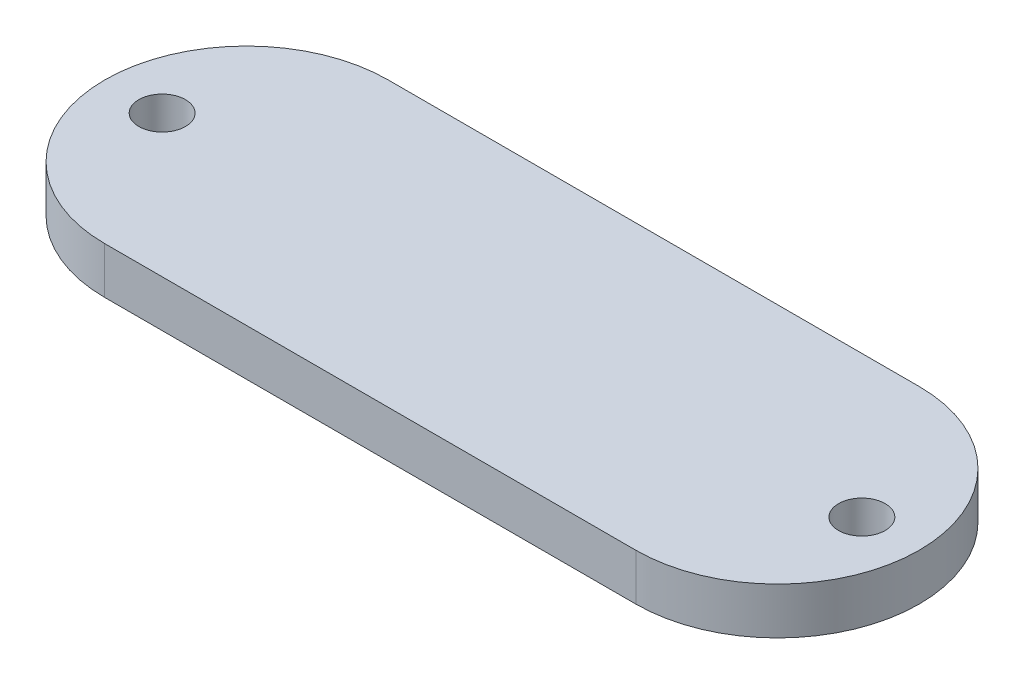
SolidWorks part; units mm, degrees
ref_plane "Front Plane" through (0, 0, 0) normal (0, 0, 1) x (1, 0, 0)
ref_plane "Top Plane" through (0, 0, 0) normal (0, 1, 0) x (1, 0, 0)
ref_plane "Right Plane" through (0, 0, 0) normal (1, 0, 0) x (0, 0, -1)
sketch "Sketch1" plane through (0, 0, 0) normal (0, 1, 0) x (1, 0, 0)
  line L1 (0, 19.75) -> (37, 19.75)
  line L2 (0, 19.75) -> (-37, 19.75)
  line L4 (0, -19.75) -> (-37, -19.75)
  line L5 (0, -19.75) -> (37, -19.75)
  arc A0 (37, -19.75) -> (37, 19.75) centre (37, 0) ccw
  arc A1 (-37, 19.75) -> (-37, -19.75) centre (-37, 0) ccw
  circle A2 centre (-48.75, 0) radius 3.25
  circle A3 centre (48.75, 0) radius 3.25
extrude "Boss-Extrude1" add sketch "Sketch1" along normal blind 6.5
